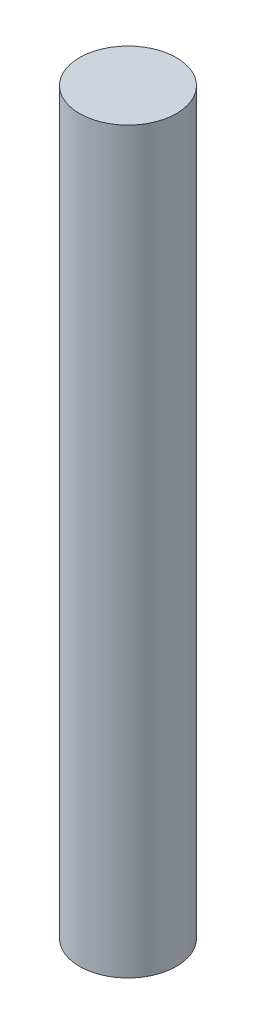
SolidWorks part; units mm, degrees
ref_plane "Front Plane" through (0, 0, 0) normal (0, 0, 1) x (1, 0, 0)
ref_plane "Top Plane" through (0, 0, 0) normal (0, 1, 0) x (1, 0, 0)
ref_plane "Right Plane" through (0, 0, 0) normal (1, 0, 0) x (0, 0, -1)
sketch "Sketch1" plane through (0, 0, 0) normal (0, 1, 0) x (1, 0, 0)
  circle A0 centre (0, 0) radius 12.5
  dimension "D1" = 25
extrude "Boss-Extrude1" add sketch "Sketch1" along normal blind 190.5
